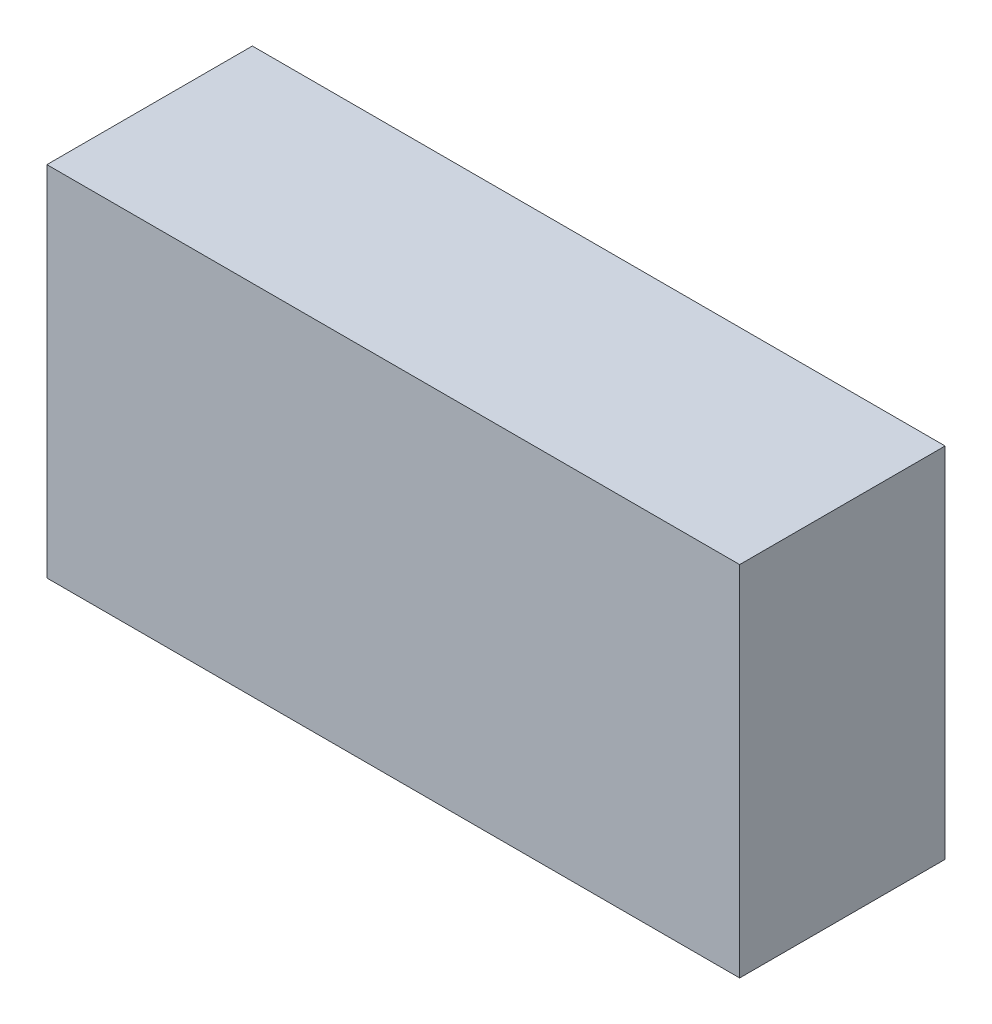
SolidWorks part; units mm, degrees
ref_plane "Front Plane" through (0, 0, 0) normal (0, 0, 1) x (1, 0, 0)
ref_plane "Top Plane" through (0, 0, 0) normal (0, 1, 0) x (1, 0, 0)
ref_plane "Right Plane" through (0, 0, 0) normal (1, 0, 0) x (0, 0, -1)
sketch "Sketch1" plane through (0, 0, 0) normal (0, 0, 1) x (1, 0, 0)
  line L1 (-28.83, -14.9) -> (28.83, -14.9)
  line L2 (-28.83, -14.9) -> (-28.83, 14.9)
  line L3 (-28.83, 14.9) -> (28.83, 14.9)
  line L4 (28.83, -14.9) -> (28.83, 14.9)
  line L5 (-28.83, -14.9) -> (28.83, 14.9) construction
  line L6 (-28.83, 14.9) -> (28.83, -14.9) construction
  point P0 (0, 0)
extrude "Envelope" add sketch "Sketch1" along normal blind 17.1
